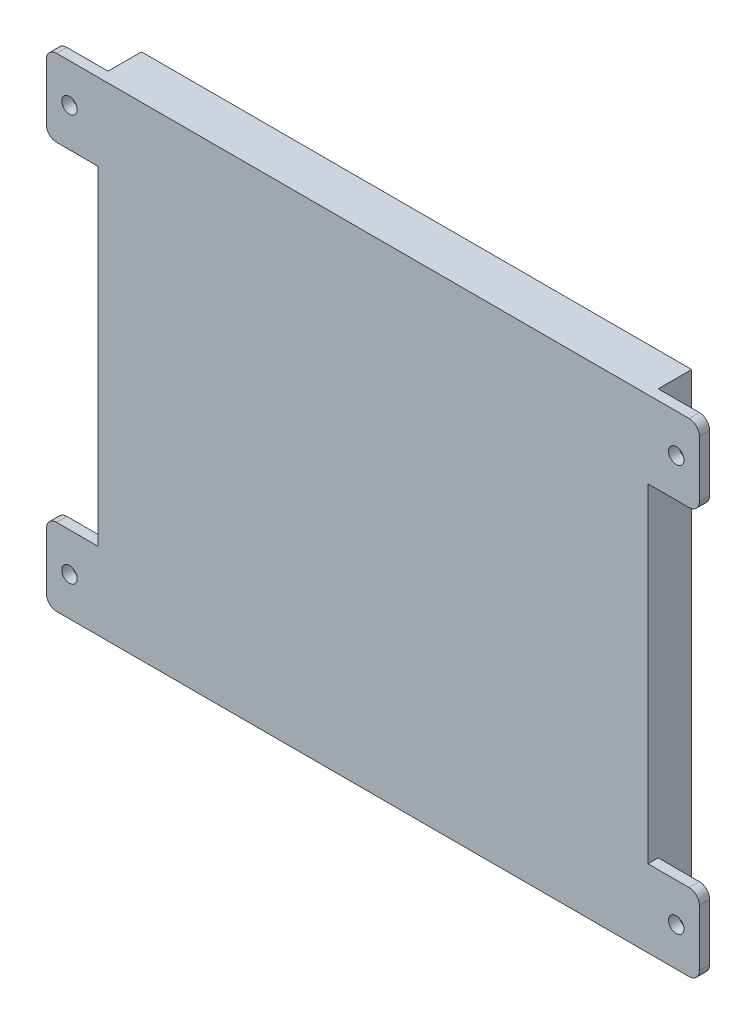
SolidWorks part; units mm, degrees
ref_plane "前视基准面" through (0, 0, 0) normal (0, 0, 1) x (1, 0, 0)
ref_plane "上视基准面" through (0, 0, 0) normal (0, 1, 0) x (1, 0, 0)
ref_plane "右视基准面" through (0, 0, 0) normal (1, 0, 0) x (0, 0, -1)
sketch "草图1" plane through (0, 0, 0) normal (0, 0, 1) x (1, 0, 0)
  line L1 (-53.5, 47) -> (53.5, 47)
  line L2 (-53.5, 47) -> (-53.5, -47)
  line L3 (-53.5, -47) -> (53.5, -47)
  line L4 (53.5, 47) -> (53.5, -47)
  dimension "D1" = 107
  dimension "D2" = 94
  dimension "D3" = 47
  dimension "D4" = 53.5
extrude "凸台-拉伸1" add sketch "草图1" along normal blind 8.5
sketch "草图2" plane through (0, 0, 0) normal (0, 0, -1) x (-1, 0, 0)
  line L0 (53.5, 47) -> (53.5, -47) construction
  line L1 (-52, 45.5) -> (52, 45.5)
  line L2 (-52, 45.5) -> (-52, -45.5)
  line L3 (-52, -45.5) -> (52, -45.5)
  line L4 (52, 45.5) -> (52, -45.5)
  line L5 (53.5, -47) -> (-53.5, -47) construction
  dimension "D1" = 91
  dimension "D2" = 104
  dimension "D3" = 1.5
  dimension "D4" = 1.5
extrude "切除-拉伸1" cut sketch "草图2" against normal blind 6.5
sketch "草图3" plane through (0, -47, 0) normal (0, -1, 0) x (1, 0, 0)
  line L0 (-53.5, 0) -> (53.5, 0) construction
  line L1 (-50, 3.5) -> (50, 3.5)
  line L2 (-50, 3.5) -> (-50, -2)
  line L3 (-50, -2) -> (50, -2)
  line L4 (50, 3.5) -> (50, -2)
  dimension "D1" = 3.5
  dimension "D2" = 100
  dimension "D3" = 50
  dimension "D4" = 2
extrude "切除-拉伸2" cut sketch "草图3" against normal blind 6
sketch "草图4" plane through (0, 0, 8.5) normal (0, 0, 1) x (1, 0, 0)
  line L0 (0, 0) -> (0, 50000) construction
  line L1 (53.5, 47) -> (63.5, 47)
  line L2 (53.5, 47) -> (53.5, 32)
  line L3 (53.5, 32) -> (63.5, 32)
  line L4 (63.5, 47) -> (63.5, 32)
  line L5 (0, 0) -> (50000, 0) construction
  line L6 (63.5, -47) -> (63.5, -32)
  line L7 (53.5, -32) -> (63.5, -32)
  line L8 (53.5, -47) -> (53.5, -32)
  line L9 (53.5, -47) -> (63.5, -47)
  line L10 (-63.5, 47) -> (-63.5, 32)
  line L11 (-53.5, 32) -> (-63.5, 32)
  line L12 (-53.5, 47) -> (-53.5, 32)
  line L13 (-53.5, 47) -> (-63.5, 47)
  line L14 (-53.5, -47) -> (-63.5, -47)
  line L15 (-53.5, -47) -> (-53.5, -32)
  line L16 (-53.5, -32) -> (-63.5, -32)
  line L17 (-63.5, -47) -> (-63.5, -32)
  dimension "D1" = 10
  dimension "D2" = 15
extrude "凸台-拉伸2" add sketch "草图4" against normal blind 2
fillet "圆角1" radius 2 8 edges at (-63.5, -47, 7.5) (-63.5, -32, 7.5) (-63.5, 47, 7.5) (-63.5, 32, 7.5) (63.5, 47, 7.5) (63.5, 32, 7.5) (63.5, -32, 7.5) (63.5, -47, 7.5)
sketch "草图5" plane through (0, 0, 6.5) normal (0, 0, -1) x (-1, 0, 0)
  line L0 (0, 47) -> (0, 50047) construction
  line L1 (-53.5, 47) -> (53.5, 47) construction
  line L2 (0, 0) -> (50000, 0) construction
  circle A0 centre (59, 39.5) radius 1.5
  circle A1 centre (59, -39.5) radius 1.5
  circle A2 centre (-59, 39.5) radius 1.5
  circle A3 centre (-59, -39.5) radius 1.5
  point P6 (0, 47)
  dimension "D1" = 39.5
  dimension "D3" = 3
  dimension "D2" = 59
extrude "切除-拉伸3" cut sketch "草图5" against normal blind 3
